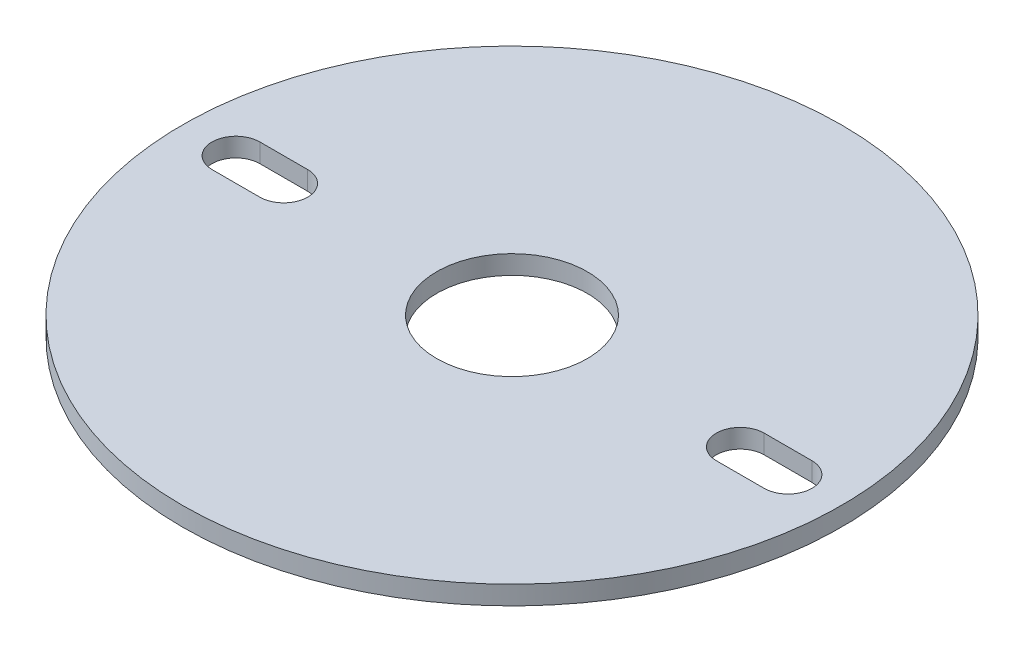
SolidWorks part; units mm, degrees
material "Plain Carbon Steel"
ref_plane "Front" through (0, 0, 0) normal (0, 0, 1) x (1, 0, 0)
ref_plane "Top" through (0, 0, 0) normal (0, 1, 0) x (1, 0, 0)
ref_plane "Right" through (0, 0, 0) normal (1, 0, 0) x (0, 0, -1)
sketch "Sketch1" plane through (0, 0, 0) normal (0, 1, 0) x (1, 0, 0)
  line L0 (6.35, 0) -> (-6.35, 0) construction
  line L1 (14.66, 1.27) -> (12.12, 1.27)
  line L2 (14.66, -1.27) -> (12.12, -1.27)
  line L3 (0, 17.5) -> (0, -17.5) construction
  line L4 (-14.66, -1.27) -> (-12.12, -1.27)
  line L5 (-14.66, 1.27) -> (-12.12, 1.27)
  circle A0 centre (0, 0) radius 17.5
  arc A1 (12.12, 1.27) -> (12.12, -1.27) centre (12.12, 0) ccw
  arc A2 (14.66, 1.27) -> (14.66, -1.27) centre (14.66, 0) cw
  arc A3 (-14.66, 1.27) -> (-14.66, -1.27) centre (-14.66, 0) ccw
  arc A4 (-12.12, 1.27) -> (-12.12, -1.27) centre (-12.12, 0) cw
  point P4 (6.35, 0)
  point P11 (10.85, 0)
  point P20 (-10.85, 0)
  dimension "D1" = 35
  dimension "D3" = 1.27
  dimension "D2" = 2.54
  dimension "D4" = 6.35
  dimension "D5" = 10.85
extrude "Boss-Extrude1" add sketch "Sketch1" along normal blind 1
sketch "Sketch2" plane through (0, 1, 0) normal (0, 1, 0) x (1, 0, 0)
  circle A0 centre (0, 0) radius 4
  dimension "D1" = 8
extrude "Cut-Extrude1" cut sketch "Sketch2" against normal mid plane 10
